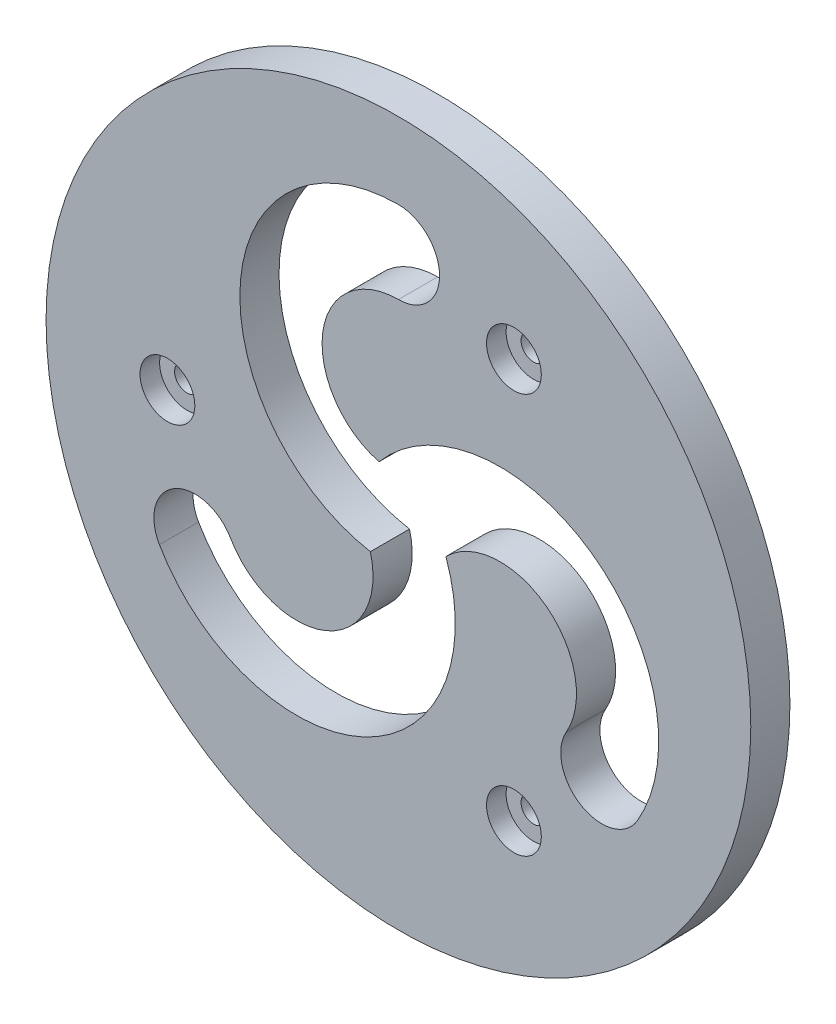
SolidWorks part; units mm, degrees
ref_plane "Alzado" through (0, 0, 0) normal (0, 0, 1) x (1, 0, 0)
ref_plane "Planta" through (0, 0, 0) normal (0, 1, 0) x (1, 0, 0)
ref_plane "Vista lateral" through (0, 0, 0) normal (1, 0, 0) x (0, 0, -1)
sketch "Croquis1" plane through (0, 0, 0) normal (0, 0, 1) x (1, 0, 0)
  circle A0 centre (0, 0) radius 45
  dimension "D1" = 90
extrude "Disco" add sketch "Croquis1" along normal blind 5
sketch "Croquis6" plane through (0, 0, 5) normal (0, 0, 1) x (1, 0, 0)
  line L6 (0, 0) -> (0, 30) construction
  circle A7 centre (0, 30) radius 5.25
  circle A8 centre (25.9808, -15) radius 5.25
  circle A9 centre (-25.9808, -15) radius 5.25
  circle A10 centre (0, 0) radius 5.25
  arc A11 (0, 30) -> (-5.169, 29.0812) centre (0, 15) ccw
  arc A12 (0, 35.25) -> (0, -5.25) centre (0, 15) ccw
  arc A13 (0, 24.75) -> (0, 5.25) centre (0, 15) ccw
  arc A14 (30.5274, -17.625) -> (-4.5466, 2.625) centre (12.9904, -7.5) ccw
  arc A15 (21.4341, -12.375) -> (4.5466, -2.625) centre (12.9904, -7.5) ccw
  arc A16 (-30.5274, -17.625) -> (4.5466, 2.625) centre (-12.9904, -7.5) ccw
  arc A17 (-21.4341, -12.375) -> (-4.5466, -2.625) centre (-12.9904, -7.5) ccw
  arc A19 (0, 30) -> (0, 0) centre (0, 15) ccw construction
  point P10 (0, 0)
  point P31 (0, 0)
  dimension "D1" = 30
  dimension "D3" = 10.5
  dimension "D5" = 5.25
  dimension "D2" = 10.5
  dimension "D4" = 15
  dimension "D6" = 5.25
  dimension "D7" = 3
extrude "PatrónGiro" cut sketch "Croquis6" against normal through all
sketch "Croquis7" plane through (0, 0, 5) normal (0, 0, 1) x (1, 0, 0)
  line L0 (0, 0) -> (-29.5, 0) construction
  circle A0 centre (-29.5, 0) radius 1.5875
  circle A1 centre (14.75, 25.5477) radius 1.5875
  circle A2 centre (14.75, -25.5477) radius 1.5875
  point P10 (0, 0)
  dimension "D2" = 3
  dimension "D1" = 29.5
extrude "BarrenosEjes" cut sketch "Croquis7" against normal blind 10
sketch "Croquis8" plane through (0, 0, 5) normal (0, 0, 1) x (1, 0, 0)
  circle A0 centre (-29.5, 0) radius 3.5
  circle A2 centre (14.75, -25.5477) radius 3.5
  circle A3 centre (14.75, 25.5477) radius 3.5
  dimension "D2" = 7
  dimension "D1" = 7
  dimension "D3" = 7
extrude "Cortar-Extruir5" cut sketch "Croquis8" against normal blind 2.5
